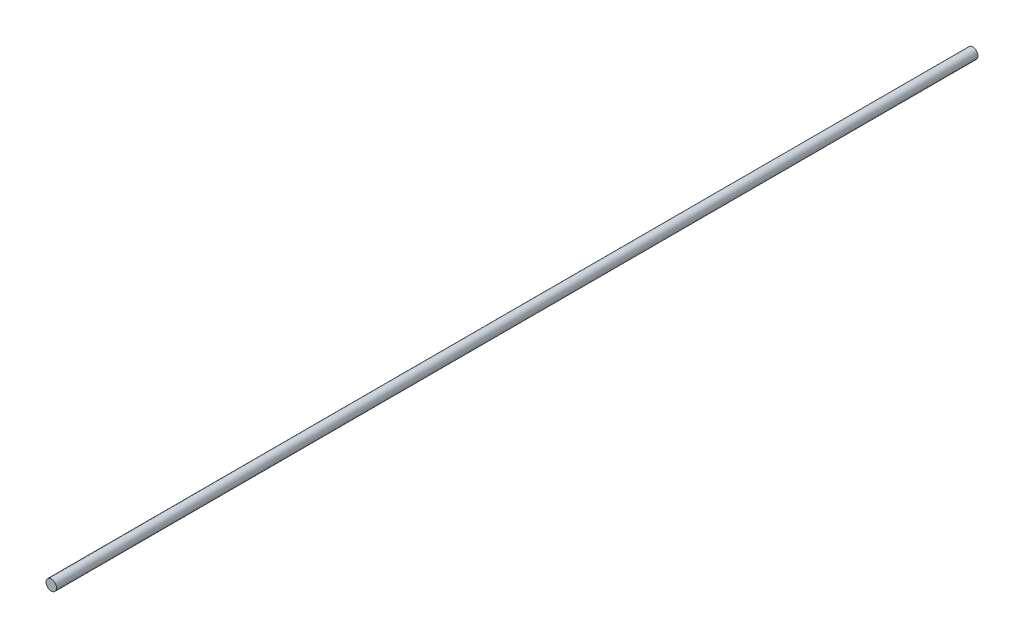
SolidWorks part; units mm, degrees
material "Plain Carbon Steel"
ref_plane "Front Plane" through (0, 0, 0) normal (0, 0, 1) x (1, 0, 0)
ref_plane "Top Plane" through (0, 0, 0) normal (0, 1, 0) x (1, 0, 0)
ref_plane "Right Plane" through (0, 0, 0) normal (1, 0, 0) x (0, 0, -1)
sketch "Sketch1" plane through (0, 0, 0) normal (0, 0, 1) x (1, 0, 0)
  circle A0 centre (0, 0) radius 2.5
  dimension "D1" = 5
extrude "Boss-Extrude1" add sketch "Sketch1" along normal mid plane 440
